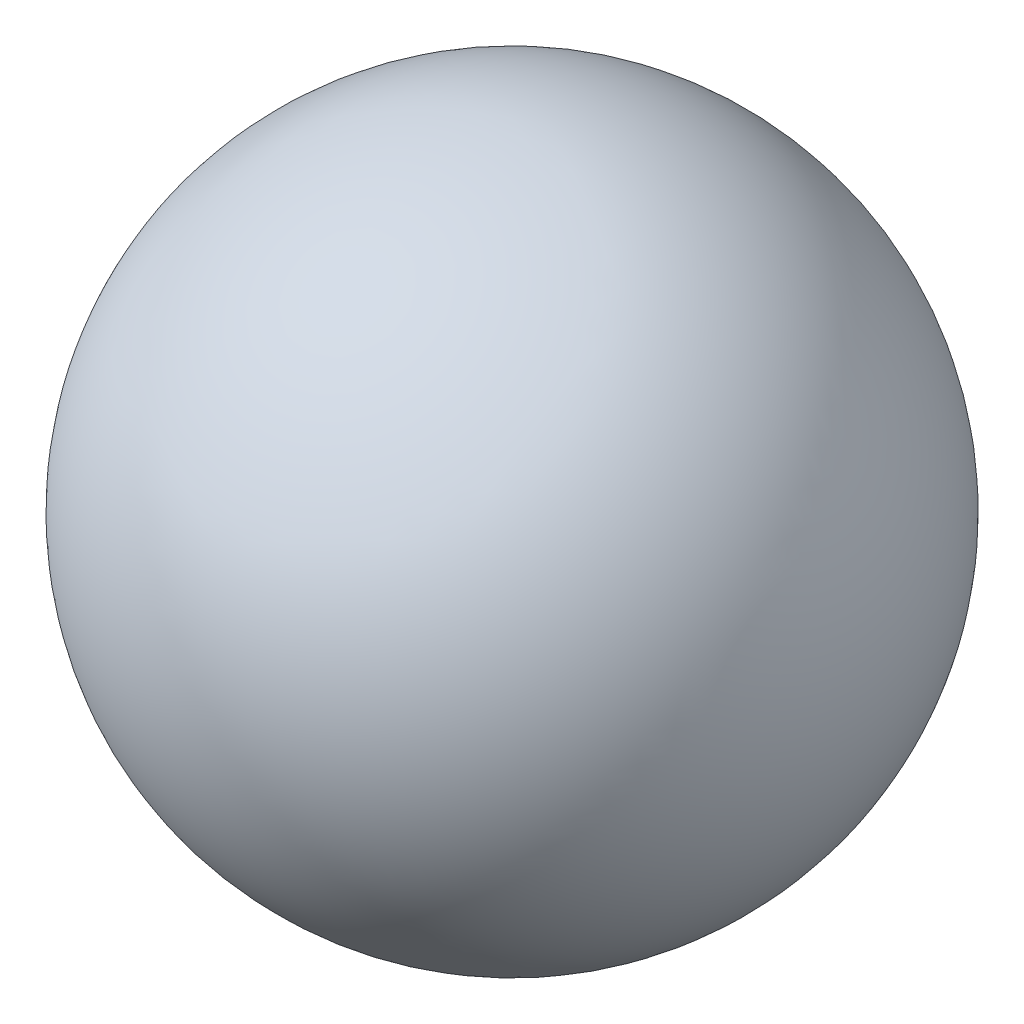
SolidWorks part; units mm, degrees
ref_plane "前视基准面" through (0, 0, 0) normal (0, 0, 1) x (1, 0, 0)
ref_plane "上视基准面" through (0, 0, 0) normal (0, 1, 0) x (1, 0, 0)
ref_plane "右视基准面" through (0, 0, 0) normal (1, 0, 0) x (0, 0, -1)
other "Configuration Table"
sketch "草图1" plane through (0, 0, 0) normal (0, 0, 1) x (1, 0, 0)
  line L0 (0, 0) -> (18, 0) construction
  line L1 (0, 0) -> (-44.9894, 0) construction
  line L2 (18, 0) -> (-18, 0)
  arc A0 (18, 0) -> (-18, 0) centre (0, 0) ccw
  dimension "D1" = 18
revolve "旋转6" add sketch "草图1" angle 360 about L2
